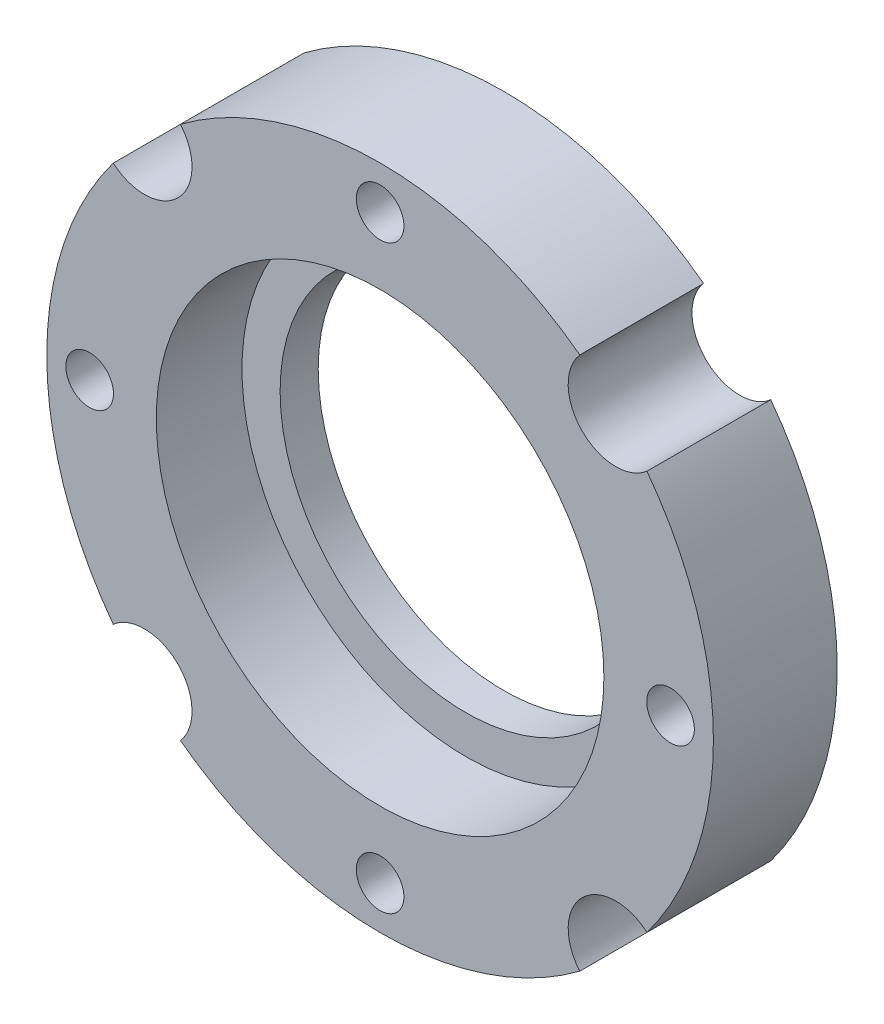
SolidWorks part; units mm, degrees
ref_plane "Płaszczyzna przednia" through (0, 0, 0) normal (0, 0, 1) x (1, 0, 0)
ref_plane "Płaszczyzna górna" through (0, 0, 0) normal (0, 1, 0) x (1, 0, 0)
ref_plane "Płaszczyzna prawa" through (0, 0, 0) normal (1, 0, 0) x (0, 0, -1)
sketch "Szkic1" plane through (0, 0, 0) normal (0, 0, 1) x (1, 0, 0)
  circle A0 centre (0, 0) radius 19.5
  circle A1 centre (0, 0) radius 35
  circle A2 centre (0, 0) radius 30.5
  point P5 (0, 30.5)
  point P6 (0, -30.5)
  dimension "D1" = 70
  dimension "D2" = 39
extrude "Dodanie-wyciągnięcie1" add sketch "Szkic1" along normal blind 13 contours A1 A2 | A2 A0
sketch "Szkic2" plane through (0, 0, 13) normal (0, 0, 1) x (1, 0, 0)
  line L0 (0, 0) -> (21.2132, 21.2132)
  line L1 (0, 0) -> (35, 0)
  line L2 (0, 0) -> (21.2132, -21.2132)
  line L3 (0, 0) -> (-21.2132, -21.2132)
  arc A0 (-22.9566, 20.0809) -> (-22.9566, -20.0809) centre (0, 0) ccw
  circle A1 centre (0, 0) radius 35 construction
  circle A2 centre (24.7487, 24.7487) radius 5
  circle A3 centre (24.7487, -24.7487) radius 5
  circle A4 centre (-24.7487, -24.7487) radius 5
  circle A6 centre (-24.7487, 24.7487) radius 5
  arc A7 (20.0809, 22.9566) -> (-20.0809, 22.9566) centre (0, 0) ccw
  arc A8 (-20.0809, -22.9566) -> (20.0809, -22.9566) centre (0, 0) ccw
  arc A9 (22.9566, -20.0809) -> (22.9566, 20.0809) centre (0, 0) ccw
  point P3 (0, 30.5)
  point P4 (0, -30.5)
  circle M1 centre (0, 0) radius 35
  dimension "D1" = 45
  dimension "D2" = 10
  dimension "D3" = 10
  dimension "D4" = 10
  dimension "D5" = 10
hole_wizard "Otwory ustalające Ø5.0mm1" positions "Szkic3" profile "Szkic4" hole size "Ø5.0" standard "ISO" end condition through all
sketch "Szkic3" plane through (0, 0, 13) normal (0, 0, 1) x (1, 0, 0)
  circle A0 centre (0, 0) radius 30.5
  point P0 (0, 30.5)
  point P3 (0, -30.5)
  point P10 (-30.5, 0)
  point P12 (30.5, 0)
sketch "Szkic4" plane through (0, 30.5, 13) normal (1, 0, 0) x (0, -1, 0)
  line L0 (0, 0) -> (0, 13)
  line L1 (0, 13) -> (2.5, 13)
  line L2 (2.5, 13) -> (2.5, 0)
  line L5 (2.5, 0) -> (0, 0)
  line L11 (0, -6.35) -> (0, 107.95) construction
  dimension "Średnica otworu na wylot" = 5
  dimension "Głębokość otworu na wylot" = 13
sketch "Szkic6" plane through (0, 0, 13) normal (0, 0, 1) x (1, 0, 0)
  circle A0 centre (0, 0) radius 23.5
  circle A1 centre (0, 0) radius 19.5
  dimension "D1" = 47
  dimension "D2" = 39
extrude "Wytnij-wyciągnięcie1" cut sketch "Szkic6" against normal blind 9
extrude "Wytnij-wyciągnięcie2" cut sketch "Szkic2" against normal blind 14 contours A4 M1 | A4 M1 | A6 M1 | A6 M1 | A2 M1 | A2 M1 | A3 M1 | A3 M1
